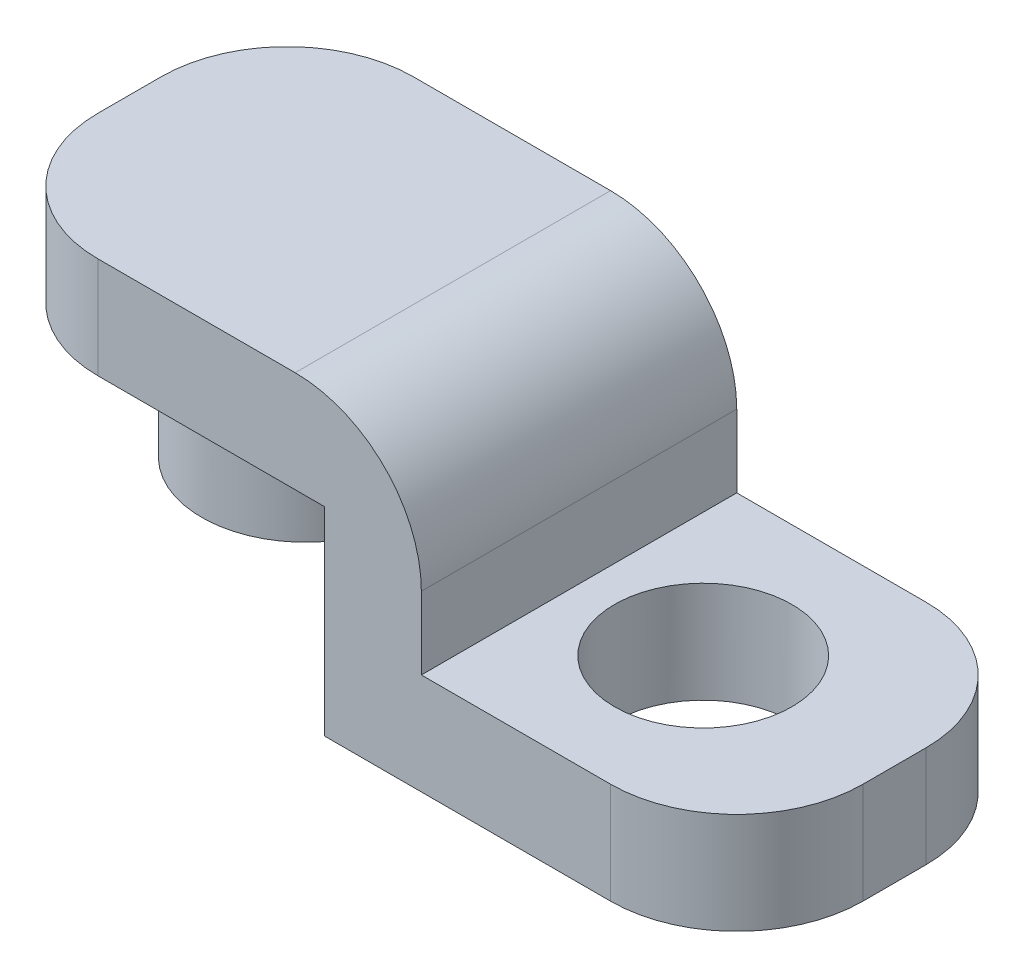
SolidWorks part; units mm, degrees
ref_plane "Front Plane" through (0, 0, 0) normal (0, 0, 1) x (1, 0, 0)
ref_plane "Top Plane" through (0, 0, 0) normal (0, 1, 0) x (1, 0, 0)
ref_plane "Right Plane" through (0, 0, 0) normal (1, 0, 0) x (0, 0, -1)
sketch "Sketch1" plane through (0, 0, 0) normal (0, 0, 1) x (1, 0, 0)
  line L0 (0, 6.04) -> (5.5, 6.04)
  line L1 (5.5, 6.04) -> (5.5, 2.04)
  line L2 (5.5, 2.04) -> (11.85, 2.04)
  line L3 (11.85, 2.04) -> (11.85, 0)
  line L4 (11.85, 0) -> (3.55, 0)
  line L5 (3.55, 0) -> (3.55, 4)
  line L6 (3.55, 4) -> (0, 4)
  line L7 (0, 4) -> (0, 6.04)
  line L8 (0, 0) -> (0, 6.04) construction
  dimension "D1" = 7.1
  dimension "D2" = 4
  dimension "D3" = 2.04
  dimension "D4" = 2.04
  dimension "D5" = 6.35
  dimension "D6" = 1.95
extrude "Boss-Extrude1" add sketch "Sketch1" along normal blind 6.35
fillet "Fillet1" radius 2.54 3 edges at (11.85, 1.02, 0) (11.85, 1.02, 6.35) (5.5, 6.04, 3.175)
sketch "Sketch2" plane through (0, 2.04, 0) normal (0, 1, 0) x (1, 0, 0)
  line L0 (8.59, -6.35) -> (8, -3.175) construction
  line L2 (8, -3.175) -> (7.41, 0) construction
  line L4 (5.5, -3.175) -> (8, -3.175) construction
  line L5 (5.5, -6.35) -> (5.5, 0) construction
  circle A0 centre (8, -3.175) radius 1.7859
  dimension "D1" = 3.5719
  dimension "D2" = 2.5
extrude "Cut-Extrude1" cut sketch "Sketch2" against normal up to next
mirror "Mirror1" [suppressed]
sketch "Sketch3" [suppressed] plane through (0, 5, 0) normal (0, -1, 0) x (1, 0, 0)
  line L0 (-3.55, 6.35) -> (3.55, 0) construction
  circle A0 centre (0, 3.175) radius 2.1
  dimension "D1" = 4.2
extrude "Boss-Extrude2" [suppressed] add sketch "Sketch3" along normal blind 2.5
sketch "Sketch4" plane through (0, 0, 0) normal (-1, 0, 0) x (0, 0, 1)
  line L4 (0, 6.04) -> (0, 4)
  line L5 (0, 4) -> (6.35, 4)
  line L6 (6.35, 4) -> (6.35, 6.04)
  line L7 (6.35, 6.04) -> (0, 6.04)
  line L8 (0, 6.04) -> (0, 4)
  line L9 (0, 4) -> (6.35, 4)
  line L10 (6.35, 4) -> (6.35, 6.04)
  line L11 (6.35, 6.04) -> (0, 6.04)
  dimension "D1" = 0
extrude "Boss-Extrude3" add sketch "Sketch4" along normal offset from surface (3.55 mm away) 7.1 up to face at (3.55, 2, 3.175) offset beyond the face yes
sketch "Sketch6" plane through (0, 4, 0) normal (0, -1, 0) x (1, 0, 0)
  line L0 (0, 3.175) -> (0, 6.35) construction
  line L1 (-3.55, 6.35) -> (3.55, 6.35) construction
  line L2 (0, 3.175) -> (0, 0) construction
  line L3 (-3.55, 0) -> (3.55, 0) construction
  circle A0 centre (0, 3.175) radius 2.1
  point P2 (0, 0)
  dimension "D1" = 4.2
extrude "Boss-Extrude5" add sketch "Sketch6" along normal blind 2.5
fillet "Fillet3" radius 2.54 2 edges at (-3.55, 5.02, 6.35) (-3.55, 5.02, 0)
